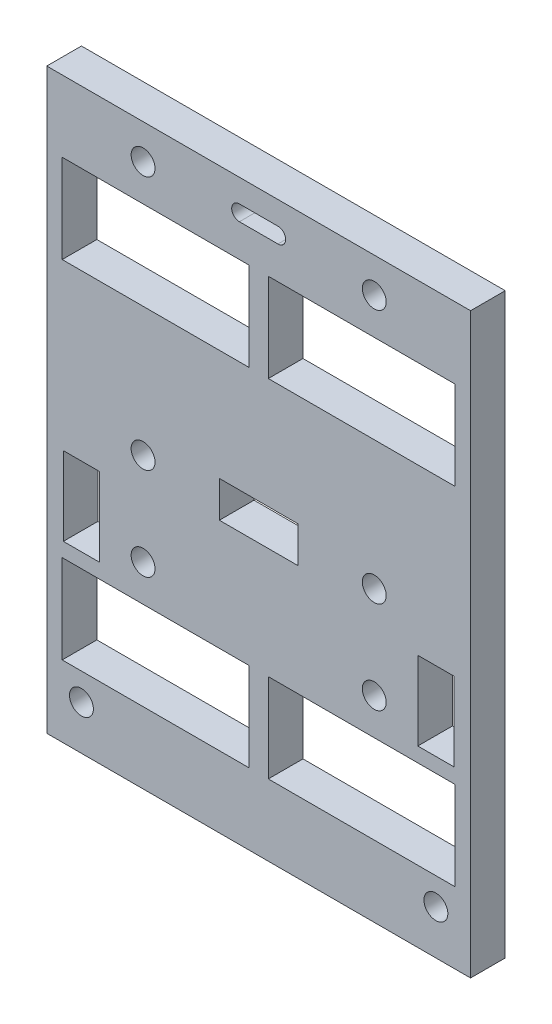
SolidWorks part; units mm, degrees
ref_plane "Front Plane" through (0, 0, 0) normal (0, 0, 1) x (1, 0, 0)
ref_plane "Top Plane" through (0, 0, 0) normal (0, 1, 0) x (1, 0, 0)
ref_plane "Right Plane" through (0, 0, 0) normal (1, 0, 0) x (0, 0, -1)
sketch "Sketch1" plane through (0, 0, 0) normal (0, 0, 1) x (1, 0, 0)
  line L0 (0, -37.5) -> (0, 37.5) construction
  line L1 (-27.5, -37.5) -> (27.5, -37.5)
  line L2 (-27.5, -37.5) -> (-27.5, 37.5)
  line L3 (-27.5, 37.5) -> (27.5, 37.5)
  line L4 (27.5, -37.5) -> (27.5, 37.5)
  line L5 (-27.5, -37.5) -> (27.5, 37.5) construction
  line L6 (-27.5, 37.5) -> (27.5, -37.5) construction
  line L7 (-27.5, 0) -> (27.5, 0) construction
  line L8 (-27.5, 22.5) -> (27.5, 22.5) construction
  line L9 (25.5, 16.75) -> (1.25, 28.25) construction
  line L10 (-25.5, 28.25) -> (-1.25, 28.25)
  line L11 (-25.5, 28.25) -> (-25.5, 16.75)
  line L12 (-25.5, 16.75) -> (-1.25, 16.75)
  line L13 (-1.25, 28.25) -> (-1.25, 16.75)
  line L14 (-25.5, 28.25) -> (-1.25, 16.75) construction
  line L15 (-25.5, 16.75) -> (-1.25, 28.25) construction
  line L16 (25.5, 28.25) -> (1.25, 16.75) construction
  line L17 (1.25, 28.25) -> (1.25, 16.75)
  line L18 (25.5, 16.75) -> (1.25, 16.75)
  line L19 (25.5, 28.25) -> (25.5, 16.75)
  line L20 (25.5, 28.25) -> (1.25, 28.25)
  line L21 (25.5, -28.25) -> (1.25, -16.75) construction
  line L22 (-25.5, -16.75) -> (-1.25, -28.25) construction
  line L23 (-25.5, -28.25) -> (-1.25, -16.75) construction
  line L24 (25.5, -16.75) -> (1.25, -28.25) construction
  line L25 (25.5, -28.25) -> (1.25, -28.25)
  line L26 (25.5, -28.25) -> (25.5, -16.75)
  line L27 (25.5, -16.75) -> (1.25, -16.75)
  line L28 (1.25, -28.25) -> (1.25, -16.75)
  line L29 (-1.25, -28.25) -> (-1.25, -16.75)
  line L30 (-25.5, -16.75) -> (-1.25, -16.75)
  line L31 (-25.5, -28.25) -> (-25.5, -16.75)
  line L32 (-25.5, -28.25) -> (-1.25, -28.25)
  point P0 (0, 0)
  point P12 (-13.375, 22.5)
  point P21 (13.375, 22.5)
  point P30 (13.375, -22.5)
  point P31 (-13.375, -22.5)
  dimension "D1" = 55
  dimension "D2" = 75
  dimension "D3" = 22.5
  dimension "D4" = 24.25
  dimension "D5" = 11.5
  dimension "D6" = 1.25
extrude "Boss-Extrude1" add sketch "Sketch1" along normal blind 4.5
sketch "Sketch2" plane through (0, 0, 4.5) normal (0, 0, 1) x (1, 0, 0)
  line L0 (0, -37.5) -> (0, 37.5) construction
  line L1 (-27.5, -37.5) -> (27.5, -37.5) construction
  line L2 (27.5, 37.5) -> (-27.5, 37.5) construction
  line L3 (-27.5, 0) -> (27.5, 0) construction
  line L4 (-27.5, 37.5) -> (-27.5, -37.5) construction
  line L5 (27.5, -37.5) -> (27.5, 37.5) construction
  line L6 (-15, 0) -> (15, 0) construction
  circle A0 centre (-15, 33) radius 1.55
  circle A1 centre (15, 33) radius 1.55
  circle A2 centre (15, 0) radius 1.55
  circle A3 centre (-15, 0) radius 1.55
  dimension "D1" = 3.1
  dimension "D7" = 3.1
  dimension "D8" = 3.1
  dimension "D2" = 15
  dimension "D3" = 33
  dimension "D4" = 30
  dimension "D5" = 15
  dimension "D6" = 0
extrude "screwHoles" cut sketch "Sketch2" against normal through all
sketch "Sketch3" plane through (0, 0, 4.5) normal (0, 0, 1) x (1, 0, 0)
  line L0 (-27.5, 9) -> (26.0486, 9) construction
  line L1 (-27.5, 37.5) -> (-27.5, -37.5) construction
  line L3 (0, 37.5) -> (0, -37.5) construction
  line L4 (27.5, 37.5) -> (-27.5, 37.5) construction
  line L5 (-27.5, -37.5) -> (27.5, -37.5) construction
  line L6 (19.1, 6.65) -> (8.9, 11.35) construction
  line L7 (-19.1, 11.35) -> (-8.9, 11.35)
  line L8 (-19.1, 11.35) -> (-19.1, 6.65)
  line L9 (-19.1, 6.65) -> (-8.9, 6.65)
  line L10 (-8.9, 11.35) -> (-8.9, 6.65)
  line L11 (-19.1, 11.35) -> (-8.9, 6.65) construction
  line L12 (-19.1, 6.65) -> (-8.9, 11.35) construction
  line L13 (19.1, 11.35) -> (8.9, 6.65) construction
  line L14 (8.9, 11.35) -> (8.9, 6.65)
  line L15 (19.1, 6.65) -> (8.9, 6.65)
  line L16 (19.1, 11.35) -> (19.1, 6.65)
  line L17 (19.1, 11.35) -> (8.9, 11.35)
  line L18 (-27.5, 37.5) -> (-27.5, -37.5) construction
  point P2 (-27.5, 0)
  point P12 (-14, 9)
  point P21 (14, 9)
  dimension "D1" = 10.2
  dimension "D2" = 4.7
  dimension "D3" = 14
  dimension "D4" = 9
extrude "BeltClamp" [suppressed] cut sketch "Sketch3" against normal through all
sketch "Sketch4" plane through (0, 0, 4.5) normal (0, 0, 1) x (1, 0, 0)
  line L0 (-27.5, 0) -> (27.5, 0) construction
  line L1 (-27.5, 37.5) -> (-27.5, -37.5) construction
  line L2 (27.5, -37.5) -> (27.5, 37.5) construction
  line L4 (-5.1, 2.35) -> (5.1, 2.35)
  line L5 (-5.1, 2.35) -> (-5.1, -2.35)
  line L6 (-5.1, -2.35) -> (5.1, -2.35)
  line L7 (5.1, 2.35) -> (5.1, -2.35)
  line L8 (-5.1, 2.35) -> (5.1, -2.35) construction
  line L9 (-5.1, -2.35) -> (5.1, 2.35) construction
  circle A0 centre (-15, 0) radius 1.55 construction
  point P6 (0, 0)
  dimension "D1" = 10.2
  dimension "D2" = 4.7
  dimension "D3" = 0
extrude "mountingPlateTab" cut sketch "Sketch4" against normal through all
sketch "Sketch5" plane through (0, 0, 4.5) normal (0, 0, 1) x (1, 0, 0)
  line L0 (-27.5, -9.75) -> (27.5, -9.75) construction
  line L1 (-27.5, 37.5) -> (-27.5, -37.5) construction
  line L2 (27.5, -37.5) -> (27.5, 37.5) construction
  line L4 (0, -37.5) -> (0, 37.5) construction
  line L5 (-27.5, -37.5) -> (27.5, -37.5) construction
  line L6 (27.5, 37.5) -> (-27.5, 37.5) construction
  line L7 (-20.65, -14.85) -> (-25.35, -4.65) construction
  line L8 (20.65, -4.65) -> (25.35, -4.65)
  line L9 (20.65, -4.65) -> (20.65, -14.85)
  line L10 (20.65, -14.85) -> (25.35, -14.85)
  line L11 (25.35, -4.65) -> (25.35, -14.85)
  line L12 (20.65, -4.65) -> (25.35, -14.85) construction
  line L13 (20.65, -14.85) -> (25.35, -4.65) construction
  line L14 (-20.65, -4.65) -> (-25.35, -14.85) construction
  line L15 (-25.35, -4.65) -> (-25.35, -14.85)
  line L16 (-20.65, -14.85) -> (-25.35, -14.85)
  line L17 (-20.65, -4.65) -> (-20.65, -14.85)
  line L18 (-20.65, -4.65) -> (-25.35, -4.65)
  line L19 (23, -9.75) -> (23, -37.5) construction
  line L20 (-23, -9.75) -> (-23, -37.5) construction
  circle A0 centre (23, -31.75) radius 1.55
  circle A1 centre (-23, -31.75) radius 1.55
  point P15 (23, -9.75)
  point P24 (-23, -9.75)
  dimension "D5" = 3.1
  dimension "D2" = 10.2
  dimension "D3" = 4.7
  dimension "D4" = 23
  dimension "D6" = 22
  dimension "D1" = 9.75
extrude "BraceTabs" cut sketch "Sketch5" against normal through all
sketch "Sketch6" plane through (0, 0, 4.5) normal (0, 0, 1) x (1, 0, 0)
  line L0 (-25.35, -9.75) -> (25.35, -9.75) construction
  line L1 (-25.35, -4.65) -> (-25.35, -14.85) construction
  line L2 (25.35, -14.85) -> (25.35, -4.65) construction
  line L3 (0, -2.35) -> (0, -37.5) construction
  line L4 (-5.1, -2.35) -> (5.1, -2.35) construction
  line L5 (-27.5, -37.5) -> (27.5, -37.5) construction
  line L6 (23, -14.85) -> (23, -4.65) construction
  line L7 (20.65, -14.85) -> (25.35, -14.85) construction
  line L8 (25.35, -4.65) -> (20.65, -4.65) construction
  line L9 (20.65, -4.65) -> (20.65, -14.85) construction
  line L10 (19.65, -15.85) -> (26.35, -15.85)
  line L11 (19.65, -15.85) -> (19.65, -3.65)
  line L12 (19.65, -3.65) -> (26.35, -3.65)
  line L13 (26.35, -15.85) -> (26.35, -3.65)
  line L14 (19.65, -15.85) -> (26.35, -3.65) construction
  line L15 (19.65, -3.65) -> (26.35, -15.85) construction
  line L16 (-19.65, -3.65) -> (-26.35, -15.85) construction
  line L17 (-19.65, -15.85) -> (-26.35, -3.65) construction
  line L18 (-23, -14.85) -> (-23, -4.65) construction
  line L19 (-26.35, -15.85) -> (-26.35, -3.65)
  line L20 (-19.65, -3.65) -> (-26.35, -3.65)
  line L21 (-19.65, -15.85) -> (-19.65, -3.65)
  line L22 (-19.65, -15.85) -> (-26.35, -15.85)
  circle A0 centre (23, -9.75) radius 1.55
  circle A1 centre (-23, -9.75) radius 1.55
  point P18 (23, -9.75)
  dimension "D3" = 3.1
  dimension "D1" = 1
  dimension "D2" = 1
extrude "FrontToRear1" [suppressed] add sketch "Sketch6" against normal up to surface (4.5 mm away)
sketch "Sketch7" plane through (0, 0, 4.5) normal (0, 0, 1) x (1, 0, 0)
  line L0 (5.1, 2.35) -> (-5.1, 2.35) construction
  line L1 (-20, -3.35) -> (20, -3.35)
  line L2 (-20, -3.35) -> (-20, 3.35)
  line L3 (-20, 3.35) -> (20, 3.35)
  line L4 (20, -3.35) -> (20, 3.35)
  line L5 (-20, -3.35) -> (20, 3.35) construction
  line L6 (-20, 3.35) -> (20, -3.35) construction
  circle A0 centre (15, 0) radius 1.55 construction
  point P0 (0, 0)
  dimension "D1" = 1
  dimension "D2" = 5
extrude "FrontToRear2" [suppressed] add sketch "Sketch7" against normal through all
sketch "Sketch8" plane through (0, 0, 4.5) normal (0, 0, 1) x (1, 0, 0)
  line L0 (-27.5, -12) -> (27.5, -12) construction
  line L1 (-27.5, 37.5) -> (-27.5, -37.5) construction
  line L2 (27.5, -37.5) -> (27.5, 37.5) construction
  line L3 (0, -37.5) -> (0, 0) construction
  line L4 (-27.5, -37.5) -> (27.5, -37.5) construction
  circle A0 centre (-15, -12) radius 1.55
  circle A1 centre (15, -12) radius 1.55
  dimension "D2" = 3.1
  dimension "D1" = 12
  dimension "D3" = 15
extrude "ExpansionScrewholes" cut sketch "Sketch8" against normal through all
sketch "Sketch12" plane through (0, 0, 4.5) normal (0, 0, 1) x (1, 0, 0)
  line L0 (0, 37.5) -> (0, 0) construction
  line L1 (27.5, 37.5) -> (-27.5, 37.5) construction
  line L2 (-2.5, 33.5) -> (2.5, 33.5) construction
  line L3 (-2.5, 34.5) -> (2.5, 34.5)
  line L4 (-2.5, 32.5) -> (2.5, 32.5)
  arc A0 (-2.5, 34.5) -> (-2.5, 32.5) centre (-2.5, 33.5) ccw
  arc A1 (2.5, 32.5) -> (2.5, 34.5) centre (2.5, 33.5) ccw
  point P7 (0, 33.5)
  dimension "D1" = 3
  dimension "D2" = 2
  dimension "D3" = 5
extrude "CableTieSlot" cut sketch "Sketch12" against normal through all
sketch "Sketch11" [suppressed] plane through (0, 0, 4.5) normal (0, 0, 1) x (1, 0, 0)
  line L0 (13.5615, -8.85) -> (27.5, -8.85) construction
  line L1 (27.5, -37.5) -> (27.5, 37.5) construction
  line L2 (0, 37.5) -> (0, -37.5) construction
  line L3 (36.5, -14.85) -> (18.5, -14.85)
  line L4 (36.5, -14.85) -> (36.5, -2.85)
  line L5 (36.5, -2.85) -> (18.5, -2.85)
  line L6 (18.5, -14.85) -> (18.5, -2.85)
  line L7 (36.5, -14.85) -> (18.5, -2.85) construction
  line L8 (36.5, -2.85) -> (18.5, -14.85) construction
  line L11 (-36.5, -2.85) -> (-18.5, -14.85) construction
  line L12 (-36.5, -14.85) -> (-18.5, -2.85) construction
  line L13 (-18.5, -14.85) -> (-18.5, -2.85)
  line L14 (-36.5, -2.85) -> (-18.5, -2.85)
  line L15 (-36.5, -14.85) -> (-36.5, -2.85)
  line L16 (-36.5, -14.85) -> (-18.5, -14.85)
  line L17 (36.5, -2.85) -> (18.5, -14.85) construction
  line L18 (20.65, -14.85) -> (25.35, -14.85) construction
  line L19 (27.5, 37.5) -> (-27.5, 37.5) construction
  line L20 (-27.5, -37.5) -> (27.5, -37.5) construction
  dimension "D1" = 9
  dimension "D2" = 12
  dimension "D3" = 0
extrude "Cut-Extrude2" [suppressed] cut sketch "Sketch11" against normal through all
sketch "Sketch10" plane through (0, 0, 4.5) normal (0, 0, 1) x (1, 0, 0)
  line L0 (4.7446, 1) -> (27.5, 1) construction
  line L1 (-5.1, 0) -> (5.1, 0) construction
  line L2 (27.5, -37.5) -> (27.5, 37.5) construction
  line L3 (0, 2.35) -> (0, -2.35) construction
  line L4 (36.5, 4) -> (18.5, 4)
  line L5 (36.5, 4) -> (36.5, -2)
  line L6 (36.5, -2) -> (18.5, -2)
  line L7 (18.5, 4) -> (18.5, -2)
  line L8 (36.5, 4) -> (18.5, -2) construction
  line L9 (36.5, -2) -> (18.5, 4) construction
  line L10 (5.1, 2.35) -> (-5.1, 2.35) construction
  line L11 (-5.1, -2.35) -> (5.1, -2.35) construction
  line L12 (-36.5, -2) -> (-18.5, 4) construction
  line L13 (-36.5, 4) -> (-18.5, -2) construction
  line L14 (-4.7446, 1) -> (-27.5, 1) construction
  line L15 (-18.5, 4) -> (-18.5, -2)
  line L16 (-36.5, -2) -> (-18.5, -2)
  line L17 (-36.5, 4) -> (-36.5, -2)
  line L18 (-36.5, 4) -> (-18.5, 4)
  line L19 (36.5, -2) -> (18.5, 4) construction
  line L20 (-5.1, 2.35) -> (-5.1, -2.35) construction
  line L21 (5.1, -2.35) -> (5.1, 2.35) construction
  dimension "D1" = 6
  dimension "D2" = 9
  dimension "D3" = 1
extrude "CableTieSlots" [suppressed] cut sketch "Sketch10" against normal through all
sketch "Sketch9" [suppressed] plane through (0, 0, 4.5) normal (0, 0, 1) x (1, 0, 0)
  line L0 (-27.5, -37.5) -> (27.5, -37.5) construction
  line L5 (-9, -42.5) -> (9, -42.5)
  line L6 (-9, -42.5) -> (-9, -34.5)
  line L7 (-7, -32.5) -> (7, -32.5)
  line L8 (9, -42.5) -> (9, -34.5)
  line L9 (-9, -42.5) -> (9, -32.5) construction
  line L10 (-9, -32.5) -> (9, -42.5) construction
  arc A0 (7, -32.5) -> (9, -34.5) centre (7, -34.5) cw
  arc A1 (-9, -34.5) -> (-7, -32.5) centre (-7, -34.5) cw
  point P9 (0, -37.5)
  line M42 (-27.5, -37.5) -> (27.5, -37.5)
  dimension "D3" = 2
  dimension "D1" = 18
  dimension "D2" = 5
extrude "RearFanSlot" [suppressed] cut sketch "Sketch9" against normal through all contours A1 L6 L8 A0 L7 M42 | L5 L8 L6 M42
sketch "Sketch13" [suppressed] plane through (0, 0, 4.5) normal (0, 0, 1) x (1, 0, 0)
  line L1 (-7, -2.85) -> (7, -2.85)
  line L2 (-7, -2.85) -> (-7, -11.85)
  line L3 (-7, -11.85) -> (7, -11.85)
  line L4 (7, -2.85) -> (7, -11.85)
  line L5 (-7, -2.85) -> (7, -11.85) construction
  line L6 (-7, -11.85) -> (7, -2.85) construction
  line L9 (0, 37.5) -> (0, -7.35) construction
  line L10 (-18.5, -2.85) -> (-27.5, -2.85) construction
  line L11 (27.5, 37.5) -> (-27.5, 37.5) construction
  line L13 (-27.5, -14.85) -> (-18.5, -14.85) construction
  point P0 (0, -7.35)
  dimension "D1" = 3
  dimension "D2" = 0
  dimension "D3" = 7
extrude "Cut-Extrude3" [suppressed] cut sketch "Sketch13" against normal through all
equation "\"X-ROD-SPACING\"=45"
equation "\"Y-ROD-SPACING\"=75"
equation "\"Z-ROD-SPACING\"=17.5"
equation "\"Y-BED-OFFSET\"=2"
equation "\"Y-BED-ROD-INSET\"=3.5"
equation "\"Y-BED-SCREW-SPACING\"=209"
equation "\"Y-BED-SCREW-CUTOUT-SLOT-HEIGHT\"=2"
equation "\"T-SLOT-NUT-FILLET-RADIUS\"=0.25"
equation "\"T-SLOT-SCREW-SHAFT-RADIUS\"=1.75"
equation "\"T-SLOT-SCREW-SHAFT-CUTOUT-LENGTH\"=10.5"
equation "\"T-SLOT-NUT-DEPTH\"=4.2"
equation "\"T-SLOT-NUT-WIDTH\"=3"
equation "\"T-SLOT-NUT-END-DISTANCE\"=8"
equation "\"ACRYLIC-THICKNESS\"=10"
equation "\"ACRYLIC-THICKNESS2\"=4.5"
equation "\"ACRYLIC-TAB-CUTOUT-SIZE\"=\"ACRYLIC-THICKNESS\"+\"ACRYLIC-TAB-TOLERANCE\"*2"
equation "\"ACRYLIC-TAB-WIDTH\"=\"ACRYLIC-THICKNESS\""
equation "\"ACRYLIC-M3-HOLE\"=3.1"
equation "\"SMOOTHROD-CAP-SCREW-DISTANCE\"=20"
equation "\"FRAME-WIDTH-INNER\"=370"
equation "\"NEMA17-HOLE-SPACING\"=31"
equation "\"NEMA17-CENTRAL-CUTOUT\"=22.5"
equation "\"Z-BRACKET-REACH\"=55"
equation "\"Z-ROD-INSET\"=16"
equation "\"TOP-BRACKET-SPACING\"=40"
equation "\"SMOOTHROD-X-LENGTH\"=350"
equation "\"SMOOTHROD-Y-LENGTH\"=350"
equation "\"SMOOTHROD-Z-LENGTH\"=350"
equation "\"SMOOTHROD-TIGHTENING-HEADROOM\"=.25"
equation "\"LEADSCREW-Z-LENGTH\"=300"
equation "\"SCREW-LENGTH-FRAME\"=\"ACRYLIC-THICKNESS\" + 10"
equation "\"SCREW-LENGTH-MOTOR\"=\"ACRYLIC-THICKNESS\" + 5"
equation "\"SCREW-HEAD-RADIUS\"=6"
equation "\"PRINTED-X-SMOOTHROD-DIAMETER\"=8.2"
equation "\"PRINTED-X-SMOOTHROD-CUTOUT\"=10"
equation "\"PRINTED-X-BASE-HEIGHT\"=10"
equation "\"PRINTED-LM8UU-CUTOUT-SIZE\"=15.25"
equation "\"PRINTED-LM8UU-CUTOUT-LENGTH\"=24.5"
equation "\"PRINTED-X-IDLER-HEIGHT\"=16"
equation "\"PSU-MOUNTING-WIDTH\"=95"
equation "\"PSU-MOUNTING-HEIGHT\"=177"
equation "\"Y-BELT-TO-ROD-DISTANCE\"=20"
equation "\"SPOOL-HOLDER-ROD-SPACING\"=150"
equation "\"D3@Sketch1\"=\"X-ROD-SPACING\"/2"
equation "\"D4@Sketch1\"=\"ACRYLIC-X-CARRIAGE-LM8UU-CUTOUT-WIDTH\""
equation "\"D1@Boss-Extrude1\"=\"ACRYLIC-THICKNESS2\""
equation "\"D1@Sketch2\"=\"ACRYLIC-M3-HOLE\""
equation "\"D1@Sketch3\"=\"ACRYLIC-TAB-CUTOUT-SIZE\""
equation "\"D2@Sketch3\"=\"ACRYLIC-THICKNESS2\"+\"ACRYLIC-TAB-TOLERANCE\"*2"
equation "\"ACRYLIC-X-CARRIAGE-WIDTH\"=55"
equation "\"ACRYLIC-X-CARRIAGE-HEIGHT\"=75"
equation "\"D1@Sketch1\"=\"ACRYLIC-X-CARRIAGE-WIDTH\""
equation "\"D2@Sketch1\"=\"ACRYLIC-X-CARRIAGE-HEIGHT\""
equation "\"ACRYLIC-X-CARRIAGE-CENTER-TAB-SPACING\"=14"
equation "\"D3@Sketch3\"=\"ACRYLIC-X-CARRIAGE-CENTER-TAB-SPACING\""
equation "\"SCREW-LENGTH-EXTRUDER\"=28"
equation "\"ACRYLIC-X-CARRIAGE-SCREW-SPACING-X\"=15"
equation "\"ACRYLIC-X-CARRIAGE-SCREW-SPACING-Y\"=33"
equation "\"D2@Sketch2\"=\"ACRYLIC-X-CARRIAGE-SCREW-SPACING-X\""
equation "\"D3@Sketch2\"=\"ACRYLIC-X-CARRIAGE-SCREW-SPACING-Y\""
equation "\"D1@Sketch4\"=\"ACRYLIC-TAB-CUTOUT-SIZE\""
equation "\"D2@Sketch4\"=\"ACRYLIC-THICKNESS2\"+\"ACRYLIC-TAB-TOLERANCE\"*2"
equation "\"D2@Sketch5\"=\"ACRYLIC-TAB-CUTOUT-SIZE\""
equation "\"D3@Sketch5\"=\"ACRYLIC-THICKNESS2\"+\"ACRYLIC-TAB-TOLERANCE\"*2"
equation "\"ACRYLIC-X-CARRIAGE-EXTRUDER-SHELF-DEPTH\"=\"ACRYLIC-X-CARRIAGE-EXTRUDER-OFFSET\" + 28"
equation "\"ACRYLIC-X-CARRIAGE-EXTRUDER-BRACE-SPACING\"=23"
equation "\"D4@Sketch5\"=\"ACRYLIC-X-CARRIAGE-EXTRUDER-BRACE-SPACING\""
equation "\"D4@Sketch2\"=\"ACRYLIC-X-CARRIAGE-SCREW-SPACING-X\"*2"
equation "\"D5@Sketch2\"=\"ACRYLIC-X-CARRIAGE-SCREW-SPACING-X\""
equation "\"D7@Sketch2\"=\"ACRYLIC-M3-HOLE\""
equation "\"D8@Sketch2\"=\"ACRYLIC-M3-HOLE\""
equation "\"ACRYLIC-X-CARRIAGE-LM8UU-CUTOUT-WIDTH\"=24.25"
equation "\"ACRYLIC-TAB-TOLERANCE\"=.1"
equation "\"ACRYLIC-X-CARRIAGE-EXTRUDER-OFFSET\"=26"
equation "\"ACRYLIC-X-CARRIAGE-EXTRUDER-ANGLE\"=90"
equation "\"ACRYLIC-X-CARRIAGE-EXTRUDER-BRACE-TAB-OFFSET\"=20"
equation "\"ACRYLIC-X-CARRIAGE-EXTRUDER-BRACE-HEIGHT\"=35"
equation "\"ACRYLIC-X-CARRIAGE-EXTRUDER-BRACE-SCREW-SPACING\"=22"
equation "\"D5@Sketch5\"=\"ACRYLIC-M3-HOLE\""
equation "\"D3@Sketch6\"=\"ACRYLIC-M3-HOLE\""
equation "\"ACRYLIC-X-CARRIAGE-LM8UU-CUTOUT-HEIGHT\"=11.5"
equation "\"ACRYLIC-X-CARRIAGE-DUAL-WIDTH-MULTIPLIER\"=1.65"
equation "\"ACRYLIC-X-CARRIAGE-DUAL-HOTEND-SPACING\"=42"
equation "\"ACRYLIC-X-CARRIAGE-DUAL-WIDTH\"=75"
equation "\"ACRYLIC-X-CARRIAGE-DUAL-HOTEND-SEPARATION\"=36"
equation "\"ACRYLIC-X-CARRIAGE-DUAL-MOUNT-PLATE-DEPTH\"=75"
equation "\"ACRYLIC-X-CARRIAGE-DUAL-MOUNT-BRACE-WIDTH\"=33"
equation "\"ACRYLIC-X-CARRIAGE-DUAL-MOUNT-SCREW-WIDTH\"=40"
equation "\"D5@Sketch1\"=\"ACRYLIC-X-CARRIAGE-LM8UU-CUTOUT-HEIGHT\""
equation "\"D2@Sketch8\"=\"ACRYLIC-M3-HOLE\""
equation "\"D1@Sketch5\"=\"ACRYLIC-THICKNESS2\"/2 + 7.5"
